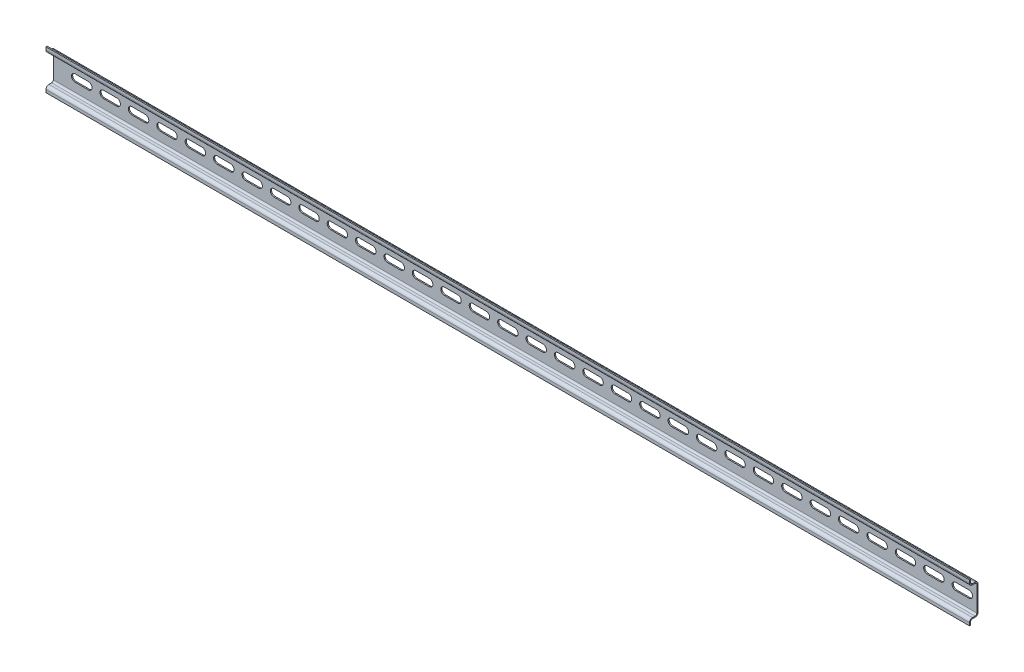
SolidWorks part; units mm, degrees
ref_plane "Front Plane" through (0, 0, 0) normal (0, 0, 1) x (1, 0, 0)
ref_plane "Top Plane" through (0, 0, 0) normal (0, 1, 0) x (1, 0, 0)
ref_plane "Right Plane" through (0, 0, 0) normal (1, 0, 0) x (0, 0, -1)
sketch "Sketch1" plane through (0, 0, 0) normal (1, 0, 0) x (0, 0, -1)
  line L0 (0, 0) -> (96.2341, 0) construction
  line L1 (0, 12.446) -> (0, -12.446)
  line L2 (0, -12.446) -> (-6.484, -12.446)
  line L3 (-6.484, -12.446) -> (-6.484, -17.526)
  line L4 (-6.484, -17.526) -> (-5.484, -17.526)
  line L5 (-5.484, -17.526) -> (-5.484, -13.462)
  line L6 (-5.484, -13.462) -> (1.016, -13.462)
  line L9 (1.016, -13.462) -> (1.016, 13.462)
  line L10 (-5.484, 17.526) -> (-5.484, 13.462)
  line L11 (-6.484, 17.526) -> (-5.484, 17.526)
  line L12 (-6.484, 12.446) -> (-6.484, 17.526)
  line L13 (0, 12.446) -> (-6.484, 12.446)
  line L14 (-5.484, 13.462) -> (1.016, 13.462)
  point P20 (1.016, 0)
  dimension "D1" = 96.2341
  dimension "D2" = 26.924
  dimension "D3" = 7.5
  dimension "D4" = 1
  dimension "D5" = 1.016
  dimension "D8" = 1.016
  dimension "D9" = 35.052
extrude "Boss-Extrude1" add sketch "Sketch1" along normal blind 1000
sketch "Sketch2" plane through (0, 0, -1.016) normal (0, 0, -1) x (-1, 0, 0)
  line L0 (-980.825, 0) -> (-969.175, 0) construction
  line L1 (-980.825, 3.175) -> (-969.175, 3.175)
  line L2 (-980.825, -3.175) -> (-969.175, -3.175)
  line L3 (-1000, -13.462) -> (-1000, 13.462) construction
  line L4 (-955.825, 0) -> (-944.175, 0) construction
  line L5 (-955.825, 3.175) -> (-944.175, 3.175)
  line L6 (-955.825, -3.175) -> (-944.175, -3.175)
  line L7 (-930.825, 0) -> (-919.175, 0) construction
  line L8 (-930.825, 3.175) -> (-919.175, 3.175)
  line L9 (-930.825, -3.175) -> (-919.175, -3.175)
  line L10 (-905.825, 0) -> (-894.175, 0) construction
  line L11 (-905.825, 3.175) -> (-894.175, 3.175)
  line L12 (-905.825, -3.175) -> (-894.175, -3.175)
  line L13 (-880.825, 0) -> (-869.175, 0) construction
  line L14 (-880.825, 3.175) -> (-869.175, 3.175)
  line L15 (-880.825, -3.175) -> (-869.175, -3.175)
  line L16 (-855.825, 0) -> (-844.175, 0) construction
  line L17 (-855.825, 3.175) -> (-844.175, 3.175)
  line L18 (-855.825, -3.175) -> (-844.175, -3.175)
  line L19 (-830.825, 0) -> (-819.175, 0) construction
  line L20 (-830.825, 3.175) -> (-819.175, 3.175)
  line L21 (-830.825, -3.175) -> (-819.175, -3.175)
  line L22 (-805.825, 0) -> (-794.175, 0) construction
  line L23 (-805.825, 3.175) -> (-794.175, 3.175)
  line L24 (-805.825, -3.175) -> (-794.175, -3.175)
  line L25 (-780.825, 0) -> (-769.175, 0) construction
  line L26 (-780.825, 3.175) -> (-769.175, 3.175)
  line L27 (-780.825, -3.175) -> (-769.175, -3.175)
  line L28 (-755.825, 0) -> (-744.175, 0) construction
  line L29 (-755.825, 3.175) -> (-744.175, 3.175)
  line L30 (-755.825, -3.175) -> (-744.175, -3.175)
  line L31 (-730.825, 0) -> (-719.175, 0) construction
  line L32 (-730.825, 3.175) -> (-719.175, 3.175)
  line L33 (-730.825, -3.175) -> (-719.175, -3.175)
  line L34 (-705.825, 0) -> (-694.175, 0) construction
  line L35 (-705.825, 3.175) -> (-694.175, 3.175)
  line L36 (-705.825, -3.175) -> (-694.175, -3.175)
  line L37 (-680.825, 0) -> (-669.175, 0) construction
  line L38 (-680.825, 3.175) -> (-669.175, 3.175)
  line L39 (-680.825, -3.175) -> (-669.175, -3.175)
  line L40 (-655.825, 0) -> (-644.175, 0) construction
  line L41 (-655.825, 3.175) -> (-644.175, 3.175)
  line L42 (-655.825, -3.175) -> (-644.175, -3.175)
  line L44 (-630.825, 0) -> (-619.175, 0) construction
  line L45 (-630.825, 3.175) -> (-619.175, 3.175)
  line L46 (-630.825, -3.175) -> (-619.175, -3.175)
  line L47 (-605.825, 0) -> (-594.175, 0) construction
  line L48 (-605.825, 3.175) -> (-594.175, 3.175)
  line L49 (-605.825, -3.175) -> (-594.175, -3.175)
  line L50 (-580.825, 0) -> (-569.175, 0) construction
  line L51 (-580.825, 3.175) -> (-569.175, 3.175)
  line L52 (-580.825, -3.175) -> (-569.175, -3.175)
  line L53 (-555.825, 0) -> (-544.175, 0) construction
  line L54 (-555.825, 3.175) -> (-544.175, 3.175)
  line L55 (-555.825, -3.175) -> (-544.175, -3.175)
  line L56 (-530.825, 0) -> (-519.175, 0) construction
  line L57 (-530.825, 3.175) -> (-519.175, 3.175)
  line L58 (-530.825, -3.175) -> (-519.175, -3.175)
  line L59 (-505.825, 0) -> (-494.175, 0) construction
  line L60 (-505.825, 3.175) -> (-494.175, 3.175)
  line L61 (-505.825, -3.175) -> (-494.175, -3.175)
  line L62 (-480.825, 0) -> (-469.175, 0) construction
  line L63 (-480.825, 3.175) -> (-469.175, 3.175)
  line L64 (-480.825, -3.175) -> (-469.175, -3.175)
  line L65 (-455.825, 0) -> (-444.175, 0) construction
  line L66 (-455.825, 3.175) -> (-444.175, 3.175)
  line L67 (-455.825, -3.175) -> (-444.175, -3.175)
  line L68 (-430.825, 0) -> (-419.175, 0) construction
  line L69 (-430.825, 3.175) -> (-419.175, 3.175)
  line L70 (-430.825, -3.175) -> (-419.175, -3.175)
  line L71 (-405.825, 0) -> (-394.175, 0) construction
  line L72 (-405.825, 3.175) -> (-394.175, 3.175)
  line L73 (-405.825, -3.175) -> (-394.175, -3.175)
  line L74 (-380.825, 0) -> (-369.175, 0) construction
  line L75 (-380.825, 3.175) -> (-369.175, 3.175)
  line L76 (-380.825, -3.175) -> (-369.175, -3.175)
  line L77 (-355.825, 0) -> (-344.175, 0) construction
  line L78 (-355.825, 3.175) -> (-344.175, 3.175)
  line L79 (-355.825, -3.175) -> (-344.175, -3.175)
  line L80 (-330.825, 0) -> (-319.175, 0) construction
  line L81 (-330.825, 3.175) -> (-319.175, 3.175)
  line L82 (-330.825, -3.175) -> (-319.175, -3.175)
  line L83 (-305.825, 0) -> (-294.175, 0) construction
  line L84 (-305.825, 3.175) -> (-294.175, 3.175)
  line L85 (-305.825, -3.175) -> (-294.175, -3.175)
  line L86 (-280.825, 0) -> (-269.175, 0) construction
  line L87 (-280.825, 3.175) -> (-269.175, 3.175)
  line L88 (-280.825, -3.175) -> (-269.175, -3.175)
  line L89 (-255.825, 0) -> (-244.175, 0) construction
  line L90 (-255.825, 3.175) -> (-244.175, 3.175)
  line L91 (-255.825, -3.175) -> (-244.175, -3.175)
  line L92 (-230.825, 0) -> (-219.175, 0) construction
  line L93 (-230.825, 3.175) -> (-219.175, 3.175)
  line L94 (-230.825, -3.175) -> (-219.175, -3.175)
  line L95 (-205.825, 0) -> (-194.175, 0) construction
  line L96 (-205.825, 3.175) -> (-194.175, 3.175)
  line L97 (-205.825, -3.175) -> (-194.175, -3.175)
  line L98 (-180.825, 0) -> (-169.175, 0) construction
  line L99 (-180.825, 3.175) -> (-169.175, 3.175)
  line L100 (-180.825, -3.175) -> (-169.175, -3.175)
  line L101 (-155.825, 0) -> (-144.175, 0) construction
  line L102 (-155.825, 3.175) -> (-144.175, 3.175)
  line L103 (-155.825, -3.175) -> (-144.175, -3.175)
  line L104 (-130.825, 0) -> (-119.175, 0) construction
  line L105 (-130.825, 3.175) -> (-119.175, 3.175)
  line L106 (-130.825, -3.175) -> (-119.175, -3.175)
  line L107 (-105.825, 0) -> (-94.175, 0) construction
  line L108 (-105.825, 3.175) -> (-94.175, 3.175)
  line L109 (-105.825, -3.175) -> (-94.175, -3.175)
  line L110 (-80.825, 0) -> (-69.175, 0) construction
  line L111 (-80.825, 3.175) -> (-69.175, 3.175)
  line L112 (-80.825, -3.175) -> (-69.175, -3.175)
  line L113 (-55.825, 0) -> (-44.175, 0) construction
  line L114 (-55.825, 3.175) -> (-44.175, 3.175)
  line L115 (-55.825, -3.175) -> (-44.175, -3.175)
  line L116 (-30.825, 0) -> (-19.175, 0) construction
  line L117 (-30.825, 3.175) -> (-19.175, 3.175)
  line L118 (-30.825, -3.175) -> (-19.175, -3.175)
  arc A0 (-980.825, 3.175) -> (-980.825, -3.175) centre (-980.825, 0) ccw
  arc A1 (-969.175, -3.175) -> (-969.175, 3.175) centre (-969.175, 0) ccw
  arc A2 (-955.825, 3.175) -> (-955.825, -3.175) centre (-955.825, 0) ccw
  arc A3 (-944.175, -3.175) -> (-944.175, 3.175) centre (-944.175, 0) ccw
  arc A4 (-930.825, 3.175) -> (-930.825, -3.175) centre (-930.825, 0) ccw
  arc A5 (-919.175, -3.175) -> (-919.175, 3.175) centre (-919.175, 0) ccw
  arc A6 (-905.825, 3.175) -> (-905.825, -3.175) centre (-905.825, 0) ccw
  arc A7 (-894.175, -3.175) -> (-894.175, 3.175) centre (-894.175, 0) ccw
  arc A8 (-880.825, 3.175) -> (-880.825, -3.175) centre (-880.825, 0) ccw
  arc A9 (-869.175, -3.175) -> (-869.175, 3.175) centre (-869.175, 0) ccw
  arc A10 (-855.825, 3.175) -> (-855.825, -3.175) centre (-855.825, 0) ccw
  arc A11 (-844.175, -3.175) -> (-844.175, 3.175) centre (-844.175, 0) ccw
  arc A12 (-830.825, 3.175) -> (-830.825, -3.175) centre (-830.825, 0) ccw
  arc A13 (-819.175, -3.175) -> (-819.175, 3.175) centre (-819.175, 0) ccw
  arc A14 (-805.825, 3.175) -> (-805.825, -3.175) centre (-805.825, 0) ccw
  arc A15 (-794.175, -3.175) -> (-794.175, 3.175) centre (-794.175, 0) ccw
  arc A16 (-780.825, 3.175) -> (-780.825, -3.175) centre (-780.825, 0) ccw
  arc A17 (-769.175, -3.175) -> (-769.175, 3.175) centre (-769.175, 0) ccw
  arc A18 (-755.825, 3.175) -> (-755.825, -3.175) centre (-755.825, 0) ccw
  arc A19 (-744.175, -3.175) -> (-744.175, 3.175) centre (-744.175, 0) ccw
  arc A20 (-730.825, 3.175) -> (-730.825, -3.175) centre (-730.825, 0) ccw
  arc A21 (-719.175, -3.175) -> (-719.175, 3.175) centre (-719.175, 0) ccw
  arc A22 (-705.825, 3.175) -> (-705.825, -3.175) centre (-705.825, 0) ccw
  arc A23 (-694.175, -3.175) -> (-694.175, 3.175) centre (-694.175, 0) ccw
  arc A24 (-680.825, 3.175) -> (-680.825, -3.175) centre (-680.825, 0) ccw
  arc A25 (-669.175, -3.175) -> (-669.175, 3.175) centre (-669.175, 0) ccw
  arc A26 (-655.825, 3.175) -> (-655.825, -3.175) centre (-655.825, 0) ccw
  arc A27 (-644.175, -3.175) -> (-644.175, 3.175) centre (-644.175, 0) ccw
  arc A28 (-630.825, 3.175) -> (-630.825, -3.175) centre (-630.825, 0) ccw
  arc A29 (-619.175, -3.175) -> (-619.175, 3.175) centre (-619.175, 0) ccw
  arc A30 (-605.825, 3.175) -> (-605.825, -3.175) centre (-605.825, 0) ccw
  arc A31 (-594.175, -3.175) -> (-594.175, 3.175) centre (-594.175, 0) ccw
  arc A32 (-580.825, 3.175) -> (-580.825, -3.175) centre (-580.825, 0) ccw
  arc A33 (-569.175, -3.175) -> (-569.175, 3.175) centre (-569.175, 0) ccw
  arc A34 (-555.825, 3.175) -> (-555.825, -3.175) centre (-555.825, 0) ccw
  arc A35 (-544.175, -3.175) -> (-544.175, 3.175) centre (-544.175, 0) ccw
  arc A36 (-530.825, 3.175) -> (-530.825, -3.175) centre (-530.825, 0) ccw
  arc A37 (-519.175, -3.175) -> (-519.175, 3.175) centre (-519.175, 0) ccw
  arc A38 (-505.825, 3.175) -> (-505.825, -3.175) centre (-505.825, 0) ccw
  arc A39 (-494.175, -3.175) -> (-494.175, 3.175) centre (-494.175, 0) ccw
  arc A40 (-480.825, 3.175) -> (-480.825, -3.175) centre (-480.825, 0) ccw
  arc A41 (-469.175, -3.175) -> (-469.175, 3.175) centre (-469.175, 0) ccw
  arc A42 (-455.825, 3.175) -> (-455.825, -3.175) centre (-455.825, 0) ccw
  arc A43 (-444.175, -3.175) -> (-444.175, 3.175) centre (-444.175, 0) ccw
  arc A44 (-430.825, 3.175) -> (-430.825, -3.175) centre (-430.825, 0) ccw
  arc A45 (-419.175, -3.175) -> (-419.175, 3.175) centre (-419.175, 0) ccw
  arc A46 (-405.825, 3.175) -> (-405.825, -3.175) centre (-405.825, 0) ccw
  arc A47 (-394.175, -3.175) -> (-394.175, 3.175) centre (-394.175, 0) ccw
  arc A48 (-380.825, 3.175) -> (-380.825, -3.175) centre (-380.825, 0) ccw
  arc A49 (-369.175, -3.175) -> (-369.175, 3.175) centre (-369.175, 0) ccw
  arc A50 (-355.825, 3.175) -> (-355.825, -3.175) centre (-355.825, 0) ccw
  arc A51 (-344.175, -3.175) -> (-344.175, 3.175) centre (-344.175, 0) ccw
  arc A52 (-330.825, 3.175) -> (-330.825, -3.175) centre (-330.825, 0) ccw
  arc A53 (-319.175, -3.175) -> (-319.175, 3.175) centre (-319.175, 0) ccw
  arc A54 (-305.825, 3.175) -> (-305.825, -3.175) centre (-305.825, 0) ccw
  arc A55 (-294.175, -3.175) -> (-294.175, 3.175) centre (-294.175, 0) ccw
  arc A56 (-280.825, 3.175) -> (-280.825, -3.175) centre (-280.825, 0) ccw
  arc A57 (-269.175, -3.175) -> (-269.175, 3.175) centre (-269.175, 0) ccw
  arc A58 (-255.825, 3.175) -> (-255.825, -3.175) centre (-255.825, 0) ccw
  arc A59 (-244.175, -3.175) -> (-244.175, 3.175) centre (-244.175, 0) ccw
  arc A60 (-230.825, 3.175) -> (-230.825, -3.175) centre (-230.825, 0) ccw
  arc A61 (-219.175, -3.175) -> (-219.175, 3.175) centre (-219.175, 0) ccw
  arc A62 (-205.825, 3.175) -> (-205.825, -3.175) centre (-205.825, 0) ccw
  arc A63 (-194.175, -3.175) -> (-194.175, 3.175) centre (-194.175, 0) ccw
  arc A64 (-180.825, 3.175) -> (-180.825, -3.175) centre (-180.825, 0) ccw
  arc A65 (-169.175, -3.175) -> (-169.175, 3.175) centre (-169.175, 0) ccw
  arc A66 (-155.825, 3.175) -> (-155.825, -3.175) centre (-155.825, 0) ccw
  arc A67 (-144.175, -3.175) -> (-144.175, 3.175) centre (-144.175, 0) ccw
  arc A68 (-130.825, 3.175) -> (-130.825, -3.175) centre (-130.825, 0) ccw
  arc A69 (-119.175, -3.175) -> (-119.175, 3.175) centre (-119.175, 0) ccw
  arc A70 (-105.825, 3.175) -> (-105.825, -3.175) centre (-105.825, 0) ccw
  arc A71 (-94.175, -3.175) -> (-94.175, 3.175) centre (-94.175, 0) ccw
  arc A72 (-80.825, 3.175) -> (-80.825, -3.175) centre (-80.825, 0) ccw
  arc A73 (-69.175, -3.175) -> (-69.175, 3.175) centre (-69.175, 0) ccw
  arc A74 (-55.825, 3.175) -> (-55.825, -3.175) centre (-55.825, 0) ccw
  arc A75 (-44.175, -3.175) -> (-44.175, 3.175) centre (-44.175, 0) ccw
  arc A76 (-30.825, 3.175) -> (-30.825, -3.175) centre (-30.825, 0) ccw
  arc A77 (-19.175, -3.175) -> (-19.175, 3.175) centre (-19.175, 0) ccw
  point P3 (-975, 0)
  point P8 (-984, 0)
  point P9 (-966, 0)
  point P15 (-950, 0)
  point P22 (-925, 0)
  point P29 (-900, 0)
  point P36 (-875, 0)
  point P43 (-850, 0)
  point P50 (-825, 0)
  point P57 (-800, 0)
  point P64 (-775, 0)
  point P71 (-750, 0)
  point P78 (-725, 0)
  point P85 (-700, 0)
  point P92 (-675, 0)
  point P99 (-650, 0)
  point P107 (-625, 0)
  point P114 (-600, 0)
  point P121 (-575, 0)
  point P128 (-550, 0)
  point P135 (-525, 0)
  point P142 (-500, 0)
  point P149 (-475, 0)
  point P156 (-450, 0)
  point P163 (-425, 0)
  point P170 (-400, 0)
  point P177 (-375, 0)
  point P184 (-350, 0)
  point P191 (-325, 0)
  point P198 (-300, 0)
  point P205 (-275, 0)
  point P212 (-250, 0)
  point P219 (-225, 0)
  point P226 (-200, 0)
  point P233 (-175, 0)
  point P240 (-150, 0)
  point P247 (-125, 0)
  point P254 (-100, 0)
  point P261 (-75, 0)
  point P268 (-50, 0)
  point P274 (-25, 0)
  dimension "D1" = 3.175
  dimension "D2" = 18
  dimension "D3" = 25
  dimension "D4" = 39
extrude "Cut-Extrude1" cut sketch "Sketch2" against normal through all
fillet "Fillet1" radius 2.54 4 edges at (500, -12.446, 6.484) (500, 12.446, 6.484) (500, -13.462, -1.016) (500, 13.462, -1.016)
fillet "Fillet2" radius 1.524 4 edges at (500, -13.462, 5.484) (500, 12.446, 0) (500, -12.446, 0) (500, 13.462, 5.484)
sketch "Sketch3" plane through (0, 0, -1.016) normal (0, 0, -1) x (-1, 0, 0)
  line L0 (-1000, -17.526) -> (0, -17.526) construction
  line L1 (-1000, 17.526) -> (-812.8, 17.526)
  line L2 (-1000, 17.526) -> (-1000, -17.526)
  line L3 (-1000, -17.526) -> (-812.8, -17.526)
  line L4 (-812.8, 17.526) -> (-812.8, -17.526)
  line L5 (0, -10.922) -> (0, 10.922) construction
  dimension "D1" = 812.8
extrude "Cut-Extrude2" cut sketch "Sketch3" against normal through all both and the other way through all
